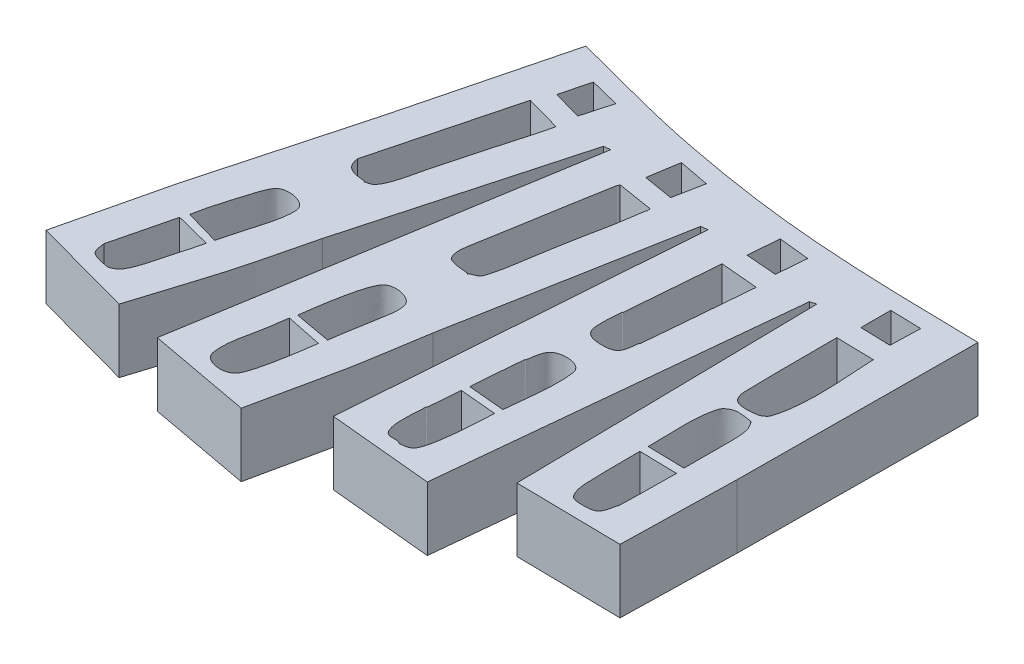
SolidWorks part; units mm, degrees
ref_plane "Front Plane" through (0, 0, 0) normal (0, 0, 1) x (1, 0, 0)
ref_plane "Top Plane" through (0, 0, 0) normal (0, 1, 0) x (1, 0, 0)
ref_plane "Right Plane" through (0, 0, 0) normal (1, 0, 0) x (0, 0, -1)
sketch "Sketch1" plane through (0, 0, 0) normal (0, 1, 0) x (1, 0, 0)
  line L0 (65.6854, -45.7865) -> (145.9282, -45.7865) construction
  line L2 (105.4165, 31.1383) -> (105.1558, -6.4062)
  line L3 (105.1558, -6.4062) -> (104.7647, -24.3962)
  line L4 (104.7647, -24.3962) -> (88.339, -24.1355)
  line L5 (88.339, -24.1355) -> (87.5568, 23.7076)
  line L6 (87.5568, 23.7076) -> (86.6443, 23.4469)
  line L7 (86.6443, 23.4469) -> (81.169, -31.0447)
  line L8 (81.169, -31.0447) -> (64.8737, -29.4804)
  line L9 (64.8737, -29.4804) -> (68.9149, 25.272)
  line L10 (68.9149, 25.272) -> (67.872, 25.1416)
  line L11 (67.872, 25.1416) -> (61.3539, -10.3171)
  line L12 (56.5305, -35.6074) -> (40.3655, -32.6091)
  line L13 (40.3655, -32.6091) -> (50.4034, 28.531)
  line L14 (50.4034, 28.531) -> (49.3605, 28.4007)
  line L15 (49.3605, 28.4007) -> (39.844, -6.1454)
  line L16 (32.8045, -31.0447) -> (17.0306, -26.7428)
  line L17 (17.0306, -26.7428) -> (21.0718, -9.7956)
  line L18 (21.0718, -9.7956) -> (27.7203, 14.5822)
  line L19 (27.7203, 14.5822) -> (34.3688, 40.6548)
  line L20 (39.844, 36.3528) -> (44.5371, 35.1795)
  line L21 (44.5371, 35.1795) -> (43.2335, 30.4865)
  line L22 (43.2335, 30.4865) -> (38.6708, 31.7901)
  line L23 (38.6708, 31.7901) -> (39.844, 36.3528)
  line L24 (57.7037, 32.3116) -> (62.5272, 31.399)
  line L25 (62.5272, 31.399) -> (61.6146, 26.706)
  line L26 (61.6146, 26.706) -> (56.9216, 27.4881)
  line L27 (56.9216, 27.4881) -> (57.7037, 32.3116)
  line L28 (75.8242, 29.7043) -> (80.6476, 29.1828)
  line L29 (80.6476, 29.1828) -> (80.2565, 24.4898)
  line L30 (80.2565, 24.4898) -> (75.4331, 24.8809)
  line L31 (75.4331, 24.8809) -> (75.8242, 29.7043)
  line L32 (37.3672, 28.9221) -> (42.9727, 27.3578)
  line L33 (31.7616, 7.4123) -> (37.3672, 28.9221)
  line L34 (94.2053, 28.6614) -> (99.0287, 28.531)
  line L35 (99.0287, 28.531) -> (98.8984, 23.838)
  line L36 (98.8984, 23.838) -> (94.2053, 23.9683)
  line L37 (94.2053, 23.9683) -> (94.2053, 28.6614)
  line L38 (55.8787, 24.4898) -> (61.4843, 23.5773)
  line L39 (61.4843, 23.5773) -> (61.6146, 23.0558)
  line L40 (74.6509, 21.7522) -> (80.5172, 21.2307)
  line L41 (93.6838, 20.7093) -> (99.5502, 20.5789)
  line L42 (99.4198, -9.0134) -> (93.6838, -8.8831)
  line L43 (31.6312, -14.8797) -> (26.156, -13.3154)
  line L44 (77.2581, -15.2708) -> (71.5222, -14.7494)
  line L45 (54.0536, -19.5728) -> (48.3176, -18.5299)
  line L46 (93.6838, -10.1867) -> (99.5502, -10.3171)
  line L47 (25.7649, -14.4887) -> (31.3705, -15.9226)
  line L48 (23.4183, -24.0051) -> (25.7649, -14.4887)
  line L49 (71.3918, -15.9226) -> (77.1278, -16.4441)
  line L50 (48.0569, -19.5728) -> (53.7929, -20.7461)
  spline S0 degree 3 poles (34.3688, 40.6548) (40.7566, 39.047) (47.0864, 37.1883) (53.5321, 35.8313) (59.4811, 34.5789) (65.4868, 33.5633) (71.5222, 32.833) (82.7525, 31.4742) (94.1059, 31.3316) (105.4165, 31.1383) knots 0 0 0 0 1 1 1 2 2 2 3 3 3 3
  spline S1 degree 3 poles (61.3539, -10.3171) (60.5564, -15.1018) (59.9234, -19.9204) (58.877, -24.657) (58.0717, -28.3021) (57.3126, -31.9573) (56.5305, -35.6074) knots 0 0 0 0 1 1 1 2 2 2 2
  spline S2 degree 3 poles (39.844, -6.1454) (38.6037, -10.974) (37.5703, -15.8635) (36.0635, -20.6157) (34.9627, -24.0875) (33.8908, -27.5684) (32.8045, -31.0447) knots 0 0 0 0 1 1 1 2 2 2 2
  spline S3 degree 3 poles (42.9727, 27.3578) (42.6098, 25.543) (42.0183, 23.7712) (41.5388, 22.0129) (40.5659, 18.4459) (39.615, 14.8641) (38.6708, 11.3232) (38.3128, 9.9807) (37.6374, 5.782) (36.3242, 5.0657) (36.0465, 4.9143) (35.7159, 4.8919) (35.4117, 4.805) knots 0 0 0 0 1 1 1 2 2 2 3 3 3 4 4 4 4
  spline S4 degree 3 poles (35.4117, 4.805) (35.3683, 4.8485) (35.3416, 4.9233) (35.2813, 4.9354) (34.8955, 5.0126) (34.4939, 4.9886) (34.1081, 5.0657) (32.6203, 5.3633) (32.0189, 5.8682) (31.7616, 7.4123) knots 0 0 0 0 1 1 1 2 2 2 3 3 3 3
  spline S5 degree 3 poles (61.6146, 23.0558) (61.5712, 23.0123) (61.4951, 22.9859) (61.4843, 22.9254) (61.1889, 21.28) (60.9974, 19.6171) (60.7021, 17.9717) (60.4799, 16.7336) (60.0077, 14.6452) (59.7895, 13.409) (59.5288, 11.9315) (59.2681, 10.4541) (59.0074, 8.9766) (58.5651, 6.4706) (58.3671, 3.9272) (57.5734, 1.546) (57.2884, 0.6909) (56.5034, 0.8671) (56.009, 0.3727) knots 0 0 0 0 1 1 1 2 2 2 3 3 3 4 4 4 5 5 5 6 6 6 6
  spline S6 degree 3 poles (56.009, 0.3727) (55.9656, 0.4161) (55.9396, 0.4949) (55.8787, 0.5031) (55.5536, 0.5464) (53.0297, 0.6407) (52.6196, 1.2852) (51.9043, 2.4092) (52.2987, 3.9943) (52.4892, 5.0657) (53.3606, 9.9671) (54.1038, 14.7799) (54.9661, 19.6664) (55.2268, 21.1438) (55.4876, 22.6213) (55.7483, 24.0987) (55.759, 24.1592) (55.8592, 24.1708) (55.8787, 24.2291) (55.9061, 24.3115) (55.8787, 24.4029) (55.8787, 24.4898) knots 0 0 0 0 1 1 1 2 2 2 3 3 3 4 4 4 5 5 5 6 6 6 7 7 7 7
  spline S7 degree 3 poles (80.5172, 21.2307) (80.0392, 15.6686) (79.6003, 10.1029) (79.0832, 4.5443) (79.0775, 4.4831) (78.963, 4.4746) (78.9529, 4.4139) (78.826, 3.6525) (78.8807, 1.9872) (77.91, 1.546) (77.5837, 1.3977) (77.2251, 1.3001) (76.8671, 1.2852) (74.9681, 1.2061) (73.2767, 1.3602) (73.2169, 3.6318) (73.1849, 4.8488) (73.2635, 6.0673) (73.3473, 7.2819) (73.3515, 7.3432) (73.4721, 7.3511) (73.4776, 7.4123) (73.9079, 12.1889) (74.2598, 16.9722) (74.6509, 21.7522) knots 0 0 0 0 1 1 1 2 2 2 3 3 3 4 4 4 5 5 5 6 6 6 7 7 7 8 8 8 8
  spline S8 degree 3 poles (99.5502, 20.5789) (99.5292, 18.1925) (100.7408, 9.6804) (99.1591, 4.9354) (99.0178, 4.5115) (98.3729, 4.0848) (97.9858, 4.0228) (97.3343, 3.9186) (94.7895, 3.5063) (94.2053, 4.6747) (94.0209, 5.0434) (93.8276, 5.4359) (93.8142, 5.8479) (93.6532, 10.7993) (93.7273, 15.7555) (93.6838, 20.7093) knots 0 0 0 0 1 1 1 2 2 2 3 3 3 4 4 4 5 5 5 5
  spline S9 degree 3 poles (93.6838, -8.8831) (93.7381, -4.9776) (93.2303, -1.8325) (94.0749, 1.546) (94.2734, 2.34) (95.3786, 2.8868) (96.1607, 2.8496) (96.8606, 2.8163) (97.5625, 2.7409) (98.2465, 2.5889) (98.4265, 2.5489) (98.5481, 2.3589) (98.6376, 2.1978) (98.8264, 1.858) (99.0648, 1.5319) (99.1591, 1.1549) (99.329, 0.4751) (99.4018, -0.2305) (99.4198, -0.9309) (99.4889, -3.6242) (99.4198, -6.3193) (99.4198, -9.0134) knots 0 0 0 0 1 1 1 2 2 2 3 3 3 4 4 4 5 5 5 6 6 6 7 7 7 7
  spline S10 degree 3 poles (26.156, -13.3154) (26.5473, -11.1629) (27.1698, -8.9703) (27.8507, -6.9276) (28.181, -5.9365) (28.5376, -4.1432) (29.2847, -3.1471) (30.1612, -1.9784) (33.0544, -2.5643) (33.717, -3.6686) (33.8584, -3.9042) (33.9663, -4.1761) (33.9777, -4.4507) (34.0665, -6.5814) (33.3414, -8.5642) (32.8045, -10.5778) (32.4111, -12.053) (32.0449, -13.4318) (31.6312, -14.8797) knots 0 0 0 0 1 1 1 2 2 2 3 3 3 4 4 4 5 5 5 6 6 6 6
  spline S11 degree 3 poles (71.5222, -14.7494) (71.7395, -12.0987) (71.9178, -9.4445) (72.174, -6.7973) (72.1799, -6.7361) (72.2915, -6.727) (72.3044, -6.6669) (72.4857, -5.8207) (72.4934, -4.085) (73.4776, -3.5382) (74.7635, -2.8238) (77.5508, -3.0117) (77.7796, -4.8418) (78.1927, -8.1469) (77.532, -12.0533) (77.2581, -15.2708) knots 0 0 0 0 1 1 1 2 2 2 3 3 3 4 4 4 5 5 5 5
  spline S12 degree 3 poles (48.3176, -18.5299) (48.4682, -17.6074) (49.3932, -9.6418) (50.7945, -7.8402) (51.7213, -6.6485) (54.6235, -7.2853) (55.2268, -8.492) (55.8006, -9.6395) (55.3934, -11.4371) (55.2268, -12.4029) (55.0096, -13.663) (54.8079, -14.926) (54.575, -16.1834) (54.3669, -17.3074) (54.2274, -18.443) (54.0536, -19.5728) knots 0 0 0 0 1 1 1 2 2 2 3 3 3 4 4 4 5 5 5 5
  spline S13 degree 3 poles (99.5502, -10.3171) (99.5067, -13.3154) (99.5054, -16.3146) (99.4198, -19.3121) (99.418, -19.3735) (99.3015, -19.3822) (99.2894, -19.4424) (99.1051, -20.3644) (99.0318, -21.7625) (97.7251, -21.9193) (97.6585, -21.9273) (95.19, -22.2702) (94.5964, -21.5282) (94.042, -20.8353) (93.862, -19.7496) (93.8142, -18.921) (93.7141, -17.1852) (93.7098, -15.445) (93.6838, -13.7065) (93.6663, -12.5333) (93.6838, -11.36) (93.6838, -10.1867) knots 0 0 0 0 1 1 1 2 2 2 3 3 3 4 4 4 5 5 5 6 6 6 7 7 7 7
  spline S14 degree 3 poles (31.3705, -15.9226) (30.9772, -17.7579) (30.4209, -19.4915) (29.9365, -21.2675) (29.4951, -22.8858) (29.203, -24.6491) (28.2418, -26.0909) (28.0279, -26.4117) (27.2093, -26.8922) (26.8078, -26.8731) (26.4958, -26.8583) (24.4443, -26.5211) (23.9398, -25.9606) (23.5046, -25.477) (23.4904, -24.5814) (23.4183, -24.0051) knots 0 0 0 0 1 1 1 2 2 2 3 3 3 4 4 4 5 5 5 5
  spline S15 degree 3 poles (77.1278, -16.4441) (77.1137, -16.6412) (76.8294, -26.002) (75.5634, -27.3946) (75.0354, -27.9754) (74.4265, -27.9481) (73.7383, -28.0464) knots 0 0 0 0 1 1 1 2 2 2 2
  spline S16 degree 3 poles (73.7383, -28.0464) (73.1325, -27.4405) (72.0165, -28.1085) (71.3918, -27.3946) (70.9276, -26.864) (70.7525, -25.5861) (70.74, -25.048) (70.7087, -23.7006) (70.7863, -22.352) (70.8704, -21.0068) (70.8742, -20.9455) (70.9945, -20.9376) (71.0007, -20.8764) (71.1697, -19.2287) (71.2615, -17.5739) (71.3918, -15.9226) knots 0 0 0 0 1 1 1 2 2 2 3 3 3 4 4 4 5 5 5 5
  spline S17 degree 3 poles (53.7929, -20.7461) (53.7097, -21.2553) (52.6819, -29.4762) (51.4463, -31.1751) (50.4846, -32.4974) (47.0812, -32.066) (46.7533, -30.2625) (46.3263, -27.9143) (47.1317, -25.3533) (47.5354, -23.0926) (47.7439, -21.925) (47.8831, -20.7461) (48.0569, -19.5728) knots 0 0 0 0 1 1 1 2 2 2 3 3 3 4 4 4 4
  dimension "D1" = 16.35
extrude "Boss-Extrude1" add sketch "Sketch1" along normal blind 10
